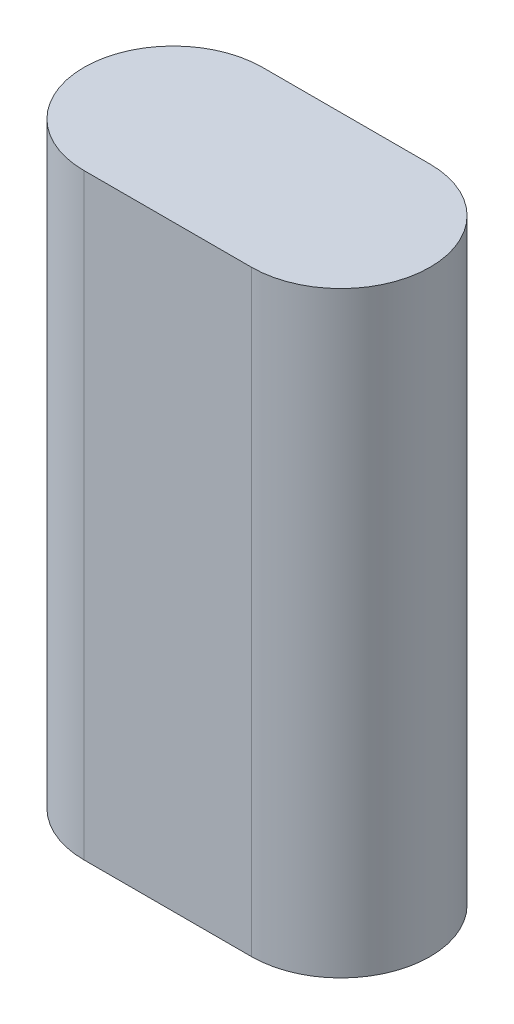
SolidWorks part; units mm, degrees
material "電池"
ref_plane "正面" through (0, 0, 0) normal (0, 0, 1) x (1, 0, 0)
ref_plane "平面" through (0, 0, 0) normal (0, 1, 0) x (1, 0, 0)
ref_plane "右側面" through (0, 0, 0) normal (1, 0, 0) x (0, 0, -1)
sketch "ｽｹｯﾁ1" plane through (0, 0, 0) normal (0, 1, 0) x (1, 0, 0)
  line L0 (-16.7, 0) -> (16.7, 0) construction
  line L1 (-16.7, 17.8) -> (16.7, 17.8)
  line L2 (-16.7, -17.8) -> (16.7, -17.8)
  arc A0 (-16.7, 17.8) -> (-16.7, -17.8) centre (-16.7, 0) ccw
  arc A1 (16.7, -17.8) -> (16.7, 17.8) centre (16.7, 0) ccw
  point P2 (0, 0)
  dimension "D1" = 17.8
  dimension "D2" = 33.4
extrude "ﾎﾞｽ - 押し出し1" add sketch "ｽｹｯﾁ1" along normal blind 119
sketch "ｽｹｯﾁ2" plane through (0, 119, 0) normal (0, 1, 0) x (1, 0, 0)
  point P1 (0, 6.3506)
